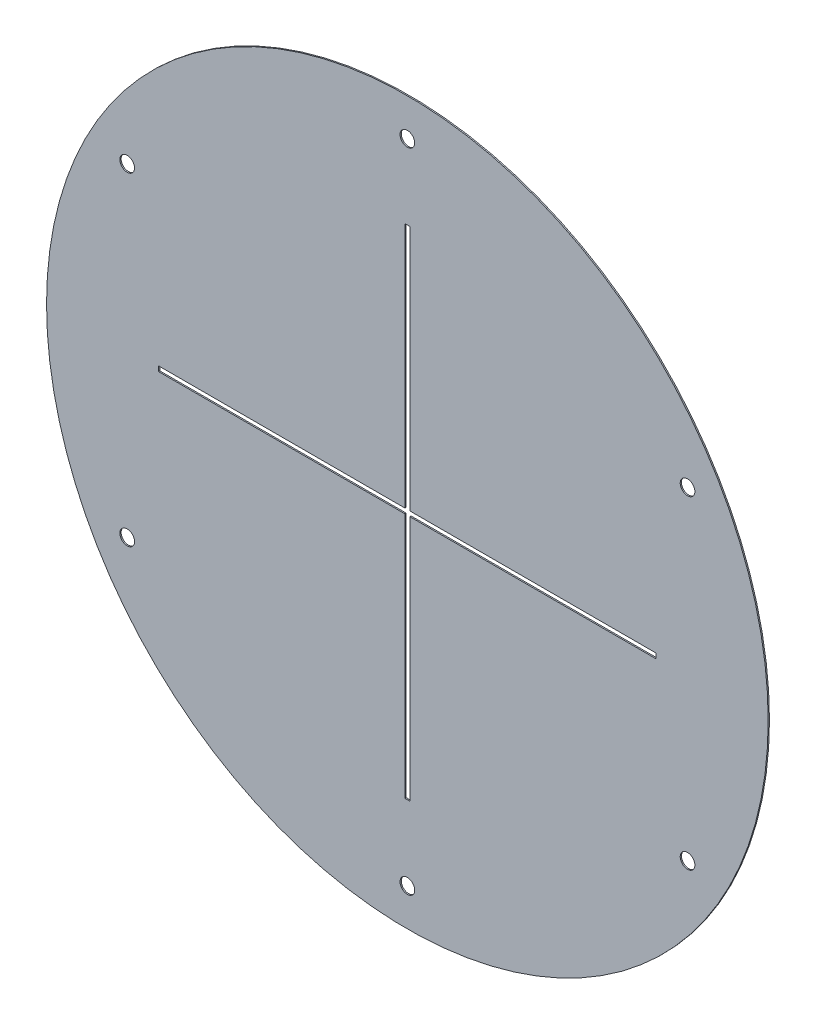
SolidWorks part; units mm, degrees
ref_plane "Front Plane" through (0, 0, 0) normal (0, 0, 1) x (1, 0, 0)
ref_plane "Top Plane" through (0, 0, 0) normal (0, 1, 0) x (1, 0, 0)
ref_plane "Right Plane" through (0, 0, 0) normal (1, 0, 0) x (0, 0, -1)
sketch "Sketch2" plane through (0, 0, 0) normal (0, 0, 1) x (1, 0, 0)
  line L0 (-0.5, 50) -> (-0.5, 0.5)
  line L9 (-0.5, 0.5) -> (-50, 0.5)
  line L10 (-50, 0.5) -> (-50, -0.5)
  line L11 (-50, -0.5) -> (-0.5, -0.5)
  line L12 (-0.5, -0.5) -> (-0.5, -50)
  line L13 (-0.5, -50) -> (0.5, -50)
  line L14 (0.5, -50) -> (0.5, -0.5)
  line L15 (0.5, -0.5) -> (50, -0.5)
  line L16 (50, -0.5) -> (50, 0.5)
  line L17 (50, 0.5) -> (0.5, 0.5)
  line L18 (0.5, 0.5) -> (0.5, 50)
  line L19 (0.5, 50) -> (-0.5, 50)
  line L20 (-72.5, 0) -> (72.5, 0) construction
  line L21 (0, 72.5) -> (0, -72.5) construction
  line L22 (-0.5, 0.5) -> (0.5, -0.5) construction
  line L23 (0.5, 0.5) -> (-0.5, -0.5) construction
  line L24 (56.2917, -32.5) -> (-56.2917, 32.5) construction
  line L25 (56.2917, 32.5) -> (-56.2917, -32.5) construction
  circle A6 centre (56.2917, -32.5) radius 1.4732
  circle A7 centre (0, -65) radius 1.4732
  circle A8 centre (-56.2917, -32.5) radius 1.4732
  circle A9 centre (-56.2917, 32.5) radius 1.4732
  circle A10 centre (0, 65) radius 1.4732
  circle A11 centre (56.2917, 32.5) radius 1.4732
  circle A12 centre (0, 0) radius 72.5
  point P2 (0, 0)
  point P3 (0, 0)
  point P4 (0, 0)
  point P21 (0, 0)
  point P22 (56.1746, 32.7019)
  point P23 (0, 0)
  point P24 (0, 0)
  dimension "D3" = 6
  dimension "D1" = 2.9464
  dimension "D9" = 145
  dimension "D2" = 65
  dimension "D5" = 130
  dimension "D6" = 1
  dimension "D7" = 100
extrude "Boss-Extrude3" add sketch "Sketch2" along normal blind 0.254
